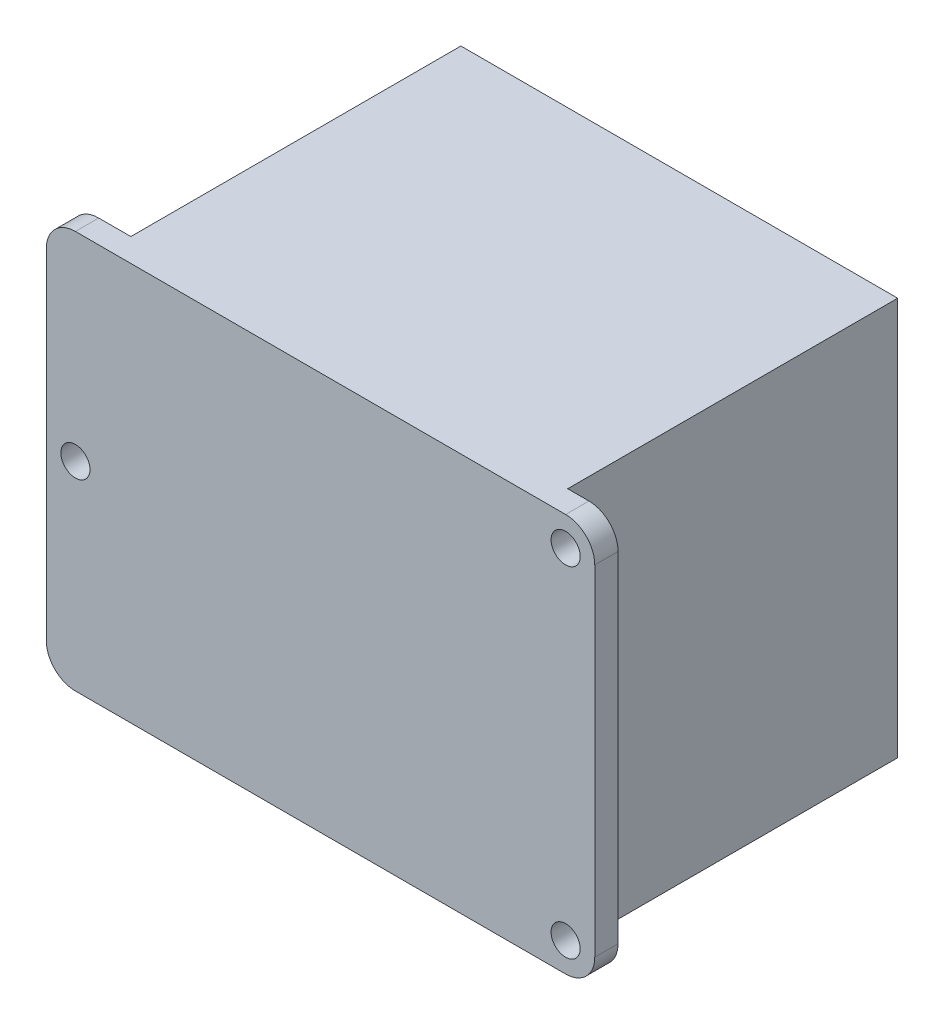
SolidWorks part; units mm, degrees
ref_plane "Front" through (0, 0, 0) normal (0, 0, 1) x (1, 0, 0)
ref_plane "Top" through (0, 0, 0) normal (0, 1, 0) x (1, 0, 0)
ref_plane "Right" through (0, 0, 0) normal (1, 0, 0) x (0, 0, -1)
sketch "草图1" plane through (0, 0, 0) normal (0, 0, 1) x (1, 0, 0)
  line L1 (0, 0) -> (56.5, 0)
  line L2 (0, 0) -> (0, -41)
  line L3 (0, -41) -> (56.5, -41)
  line L4 (56.5, 0) -> (56.5, -41)
  dimension "D1" = 56.5
  dimension "D2" = 41
extrude "凸台-拉伸1" add sketch "草图1" along normal blind 2.4
sketch "草图2" plane through (0, 0, 2.4) normal (0, 0, 1) x (1, 0, 0)
  line L0 (0, -20.5) -> (56.5, -20.5) construction
  line L1 (0, 0) -> (0, -41) construction
  line L2 (56.5, -41) -> (56.5, 0) construction
  line L3 (53.5, 0) -> (53.5, -41) construction
  line L4 (56.5, 0) -> (0, 0) construction
  line L5 (0, -41) -> (56.5, -41) construction
  circle A0 centre (53.5, -3) radius 1.5
  circle A1 centre (53.5, -38) radius 1.5
  circle A2 centre (3, -20.5) radius 1.5
  point P12 (50.4954, -38.3003)
  point P19 (50.4954, -3.8376)
  dimension "D1" = 3
  dimension "D2" = 3
  dimension "D3" = 3
  dimension "D4" = 3
  dimension "D5" = 3
  dimension "D6" = 3
  dimension "D7" = 3
extrude "切除-拉伸1" cut sketch "草图2" against normal through all and the other way through all
sketch "草图3" plane through (0, 0, 0) normal (0, 0, -1) x (-1, 0, 0)
  line L0 (0, -41) -> (-56.5, -41) construction
  line L1 (-6.3093, -41) -> (-51.3093, -41)
  line L2 (-6.3093, -41) -> (-6.3093, 0)
  line L3 (-6.3093, 0) -> (-51.3093, 0)
  line L4 (-51.3093, -41) -> (-51.3093, 0)
  line L5 (-56.5, 0) -> (0, 0) construction
  dimension "D1" = 45
extrude "凸台-拉伸2" add sketch "草图3" along normal blind 34
fillet "圆角1" radius 3 4 edges at (56.5, -41, 1.2) (56.5, 0, 1.2) (0, 0, 1.2) (0, -41, 1.2)
